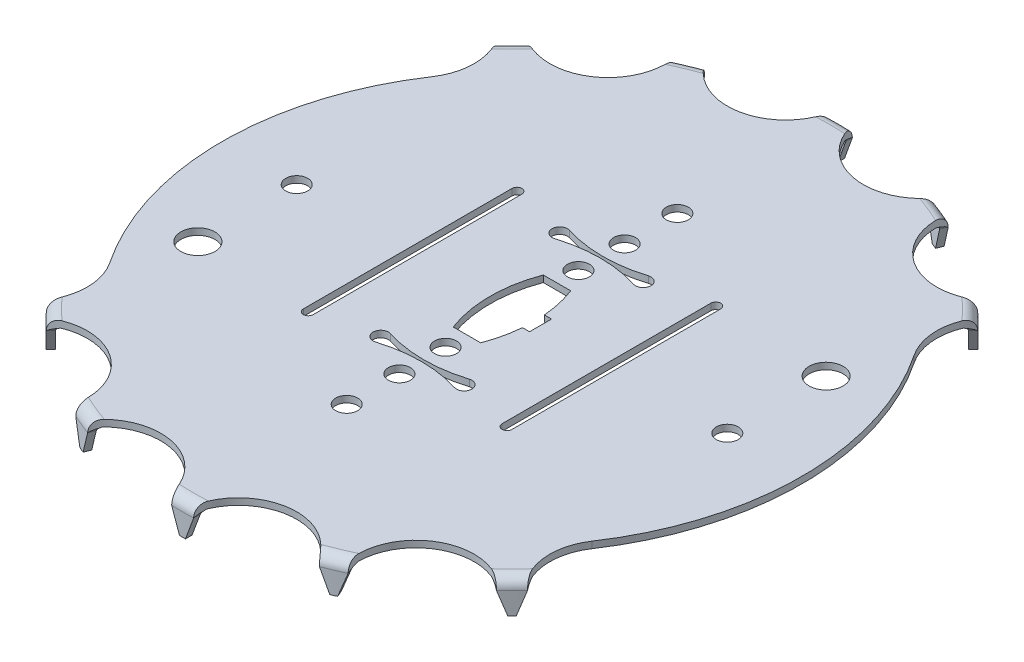
SolidWorks part; units mm, degrees
material "A-Glass Fiber"
ref_plane "Front Plane" through (0, 0, 0) normal (0, 0, 1) x (1, 0, 0)
ref_plane "Top Plane" through (0, 0, 0) normal (0, 1, 0) x (1, 0, 0)
ref_plane "Right Plane" through (0, 0, 0) normal (1, 0, 0) x (0, 0, -1)
ref_axis "Axis1" through (0, -1.5774, 0) along (0, 1, 0)
sketch "Sketch6" plane through (0, 0, 0) normal (0, 0, 1) x (1, 0, 0)
  line L0 (0, 0) -> (14.5, 0)
  line L1 (14.52, 0) -> (-14.52, 0) construction
  line L2 (15, -0.5) -> (15, -1.5)
  line L3 (0, -0.8514) -> (0, 0.8514) construction
  arc A0 (14.5, 0) -> (15, -0.5) centre (14.5, -0.5) cw
  point P8 (15, 0)
  dimension "D2" = 0.5
  dimension "D1" = 1.5
  dimension "D3" = 15
revolve "Revolve-Thin1" add sketch "Sketch6" angle 360 about axis through (0, -1.5774, 0) along (0, 1, 0)
sketch "Sketch1" plane through (0, 0, 0) normal (0, 1, 0) x (1, 0, 0)
  line L0 (-10.6066, 10.6066) -> (10.6066, -10.6066) construction
  line L1 (-5.7403, 13.8582) -> (5.7403, -13.8582) construction
  line L2 (5.7403, 13.8582) -> (-5.7403, -13.8582) construction
  line L3 (10.6066, 10.6066) -> (-10.6066, -10.6066) construction
  line L5 (0, -0.8514) -> (0, 0.8514) construction
  arc A0 (10.9543, 10.2472) -> (10.2472, 10.9543) centre (0, 0) ccw
  arc A1 (0.5, 14.9917) -> (-0.5, 14.9917) centre (0, 0) ccw
  arc A2 (-5.2751, -14.0418) -> (-0.5, -14.9917) centre (-3.0924, -15.5465) cw
  arc A3 (-10.2472, -10.9543) -> (-6.199, -13.6592) centre (-8.8064, -13.1797) cw
  arc A4 (0.5, -14.9917) -> (5.2751, -14.0418) centre (3.0924, -15.5465) cw
  arc A5 (6.199, -13.6592) -> (10.2472, -10.9543) centre (8.8064, -13.1797) cw
  arc A6 (10.9543, -10.2472) -> (10.9754, -7.3335) centre (13.1797, -8.8064) cw
  arc A7 (-10.9543, -10.2472) -> (-10.9754, -7.3335) centre (-13.1797, -8.8064) ccw
  arc A8 (-10.2472, 10.9543) -> (-6.199, 13.6592) centre (-8.8064, 13.1797) ccw
  arc A9 (-5.2751, 14.0418) -> (-0.5, 14.9917) centre (-3.0924, 15.5465) ccw
  arc A10 (0.5, 14.9917) -> (5.2751, 14.0418) centre (3.0924, 15.5465) ccw
  arc A11 (6.199, 13.6592) -> (10.2472, 10.9543) centre (8.8064, 13.1797) ccw
  arc A12 (10.9543, 10.2472) -> (10.9754, 7.3335) centre (13.1797, 8.8064) ccw
  arc A13 (-10.9543, 10.2472) -> (-10.9754, 7.3335) centre (-13.1797, 8.8064) cw
  arc A14 (6.199, 13.6592) -> (5.2751, 14.0418) centre (0, 0) ccw
  arc A15 (-5.2751, 14.0418) -> (-6.199, 13.6592) centre (0, 0) ccw
  arc A16 (-10.2472, 10.9543) -> (-10.9543, 10.2472) centre (0, 0) ccw
  arc A17 (-6.199, -13.6592) -> (-5.2751, -14.0418) centre (0, 0) ccw
  arc A18 (-0.5, -14.9917) -> (0.5, -14.9917) centre (0, 0) ccw
  arc A19 (5.2751, -14.0418) -> (6.199, -13.6592) centre (0, 0) ccw
  arc A20 (10.2472, -10.9543) -> (10.9543, -10.2472) centre (0, 0) ccw
  arc A21 (-10.9754, 7.3335) -> (-10.9754, -7.3335) centre (0, 0) ccw
  arc A22 (10.9754, -7.3335) -> (10.9754, 7.3335) centre (0, 0) ccw
  arc A23 (-10.9543, -10.2472) -> (-10.2472, -10.9543) centre (0, 0) ccw
  circle A24 centre (0, 0) radius 13.2 construction
  dimension "D2" = 30
  dimension "D3" = 45
  dimension "D9" = 0.5
  dimension "D22" = 0.5
  dimension "D25" = 13.2
  dimension "D26" = 15
  dimension "D4" = 45
  dimension "D5" = 0.5
  dimension "D6" = 22.5
  dimension "D7" = 0.5
  dimension "D8" = 0.5
  dimension "D10" = 1
  dimension "D11" = 0.5
  dimension "D12" = 0.5
  dimension "D13" = 0.5
  dimension "D14" = 0.5
  dimension "D15" = 0.5
  dimension "D16" = 45
  dimension "D17" = 0.5
  dimension "D18" = 0.5
  dimension "D19" = 0.5
  dimension "D20" = 0.5
  dimension "D21" = 0.5
  dimension "D23" = 0.5
  dimension "D24" = 0.5
extrude "Extrude3" cut sketch "Sketch1" against normal through all flip side to cut
ref_plane "Plane2" through (0, 0, 15) normal (0, 0, 1) x (1, 0, 0)
sketch "Sketch8" plane through (0, 0, 15) normal (0, 0, 1) x (1, 0, 0)
  line L0 (-0.5, -0.5) -> (-0.136, -1.5)
  line L1 (-0.5, -1.5) -> (0.5, -1.5) construction
  line L2 (-0.136, -1.5) -> (0.136, -1.5)
  line L3 (0.136, -1.5) -> (0.5, -0.5)
  line L4 (0.6632, -0.3) -> (0.6632, -1.8)
  line L5 (-0.6632, -0.3) -> (-0.6632, -1.8)
  line L6 (-0.6632, -1.8) -> (0.6632, -1.8)
  line L7 (14.52, 0) -> (-14.52, 0) construction
  arc A0 (0.5, -0.5) -> (0.6632, -0.3) centre (0.8686, -0.6342) cw
  arc A1 (-0.5, -0.5) -> (-0.6632, -0.3) centre (-0.8686, -0.6342) ccw
  dimension "D1" = 40
  dimension "D2" = 1.8
extrude "Extrude4" cut sketch "Sketch8" against normal blind 2
pattern_circular "CirPattern1" count 16 over 360 about axis through (0, 0, 0) along (0, 1, 0) of "Extrude4"
sketch "Sketch10" plane through (0, 0, 0) normal (0, 1, 0) x (1, 0, 0)
  line L0 (0, -0.825) -> (0, 0.825) construction
  line L1 (-0.825, 0) -> (0.825, 0) construction
  circle A0 centre (0, 3.025) radius 0.5
  circle A1 centre (0, 5.125) radius 0.5
  circle A2 centre (0, 7.525) radius 0.5
  circle A3 centre (0, -3.025) radius 0.5
  circle A4 centre (0, -5.125) radius 0.5
  circle A5 centre (0, -7.525) radius 0.5
  dimension "D1" = 1
  dimension "D2" = 6.05
  dimension "D3" = 15.05
  dimension "D4" = 7.525
  dimension "D5" = 3.025
  dimension "D6" = 10.25
  dimension "D7" = 5.125
extrude "Extrude5" cut sketch "Sketch10" against normal through all
sketch "Sketch11" plane through (0, 0, 0) normal (0, 1, 0) x (1, 0, 0)
  line L0 (-4.525, 4.75) -> (-4.525, -4.75) construction
  line L1 (-4.3, 4.75) -> (-4.3, -4.75)
  line L2 (-4.75, 4.75) -> (-4.75, -4.75)
  line L3 (4.525, 4.75) -> (4.525, -4.75) construction
  line L4 (4.75, 4.75) -> (4.75, -4.75)
  line L5 (4.3, 4.75) -> (4.3, -4.75)
  line L6 (-0.825, 0) -> (0.825, 0) construction
  line L7 (0, -0.825) -> (0, 0.825) construction
  arc A0 (-4.3, 4.75) -> (-4.75, 4.75) centre (-4.525, 4.75) ccw
  arc A1 (-4.75, -4.75) -> (-4.3, -4.75) centre (-4.525, -4.75) ccw
  arc A2 (4.75, 4.75) -> (4.3, 4.75) centre (4.525, 4.75) ccw
  arc A3 (4.3, -4.75) -> (4.75, -4.75) centre (4.525, -4.75) ccw
  arc A4 (-1.7953, 4.409) -> (-1.7953, 3.741) centre (-1.9, 4.075) ccw
  arc A5 (1.7953, 3.741) -> (1.7953, 4.409) centre (1.9, 4.075) ccw
  arc A6 (1.7953, -4.409) -> (1.7953, -3.741) centre (1.9, -4.075) ccw
  arc A7 (-1.7953, -3.741) -> (-1.7953, -4.409) centre (-1.9, -4.075) ccw
  arc A8 (-1.7953, 4.409) -> (1.7953, 4.409) centre (0, 10.1341) ccw
  arc A9 (1.7953, 3.741) -> (-1.7953, 3.741) centre (0, -1.9841) ccw
  arc A10 (-1.7953, -3.741) -> (1.7953, -3.741) centre (0, 1.9841) ccw
  arc A11 (-1.7953, -4.409) -> (1.7953, -4.409) centre (0, -10.1341) cw
  circle A12 centre (0, 3.025) radius 0.5 construction
  point P2 (-4.525, 0)
  point P7 (4.525, 0)
  dimension "D7" = 4.075
  dimension "D8" = 1.05
  dimension "D10" = 3.8
  dimension "D9" = 0.35
  dimension "D11" = 6
  dimension "D12" = 6
  dimension "D1" = 0.45
  dimension "D2" = 9.5
  dimension "D3" = 4.75
  dimension "D4" = 8.6
  dimension "D5" = 4.3
  dimension "D6" = 9.5
  dimension "D13" = 4.075
extrude "Extrude6" cut sketch "Sketch11" against normal blind 9.8
sketch "Sketch12" plane through (0, 0, 0) normal (0, 1, 0) x (1, 0, 0)
  line L0 (-0.825, 0) -> (0.825, 0) construction
  line L1 (0, -0.825) -> (0, 0.825) construction
  circle A0 centre (-9.8, 0) radius 0.5
  circle A1 centre (9.8, 0) radius 0.5
  circle A2 centre (9.8, 4.5) radius 0.775
  circle A3 centre (-9.8, -4.5) radius 0.775
  dimension "D1" = 1
  dimension "D2" = 1.55
  dimension "D3" = 4.5
  dimension "D4" = 4.5
  dimension "D5" = 19.6
  dimension "D6" = 9.8
extrude "Extrude7" cut sketch "Sketch12" against normal blind 9.8
sketch "Sketch13" plane through (0, 0, 0) normal (0, 1, 0) x (1, 0, 0)
  line L0 (-0.625, -2.05) -> (0.625, -2.05)
  line L1 (-0.625, 2.05) -> (0.625, 2.05)
  line L2 (-0.825, 0) -> (0.825, 0) construction
  line L3 (0, -0.825) -> (0, 0.825) construction
  line L4 (0.9778, 0.5) -> (1.3, 0.5)
  line L5 (1.3, 0.5) -> (1.3, -0.5)
  line L6 (1.3, -0.5) -> (0.9778, -0.5)
  arc A0 (0.625, 2.05) -> (0.9778, 0.5) centre (-4.8006, 0) cw
  arc A1 (-0.625, 2.05) -> (-0.9994, 0) centre (4.8006, 0) ccw
  arc A2 (-0.9994, 0) -> (-0.625, -2.05) centre (4.8006, 0) ccw
  arc A3 (0.9778, -0.5) -> (0.625, -2.05) centre (-4.8006, 0) cw
  dimension "D4" = 5.8
  dimension "D1" = 4.1
  dimension "D2" = 1.25
  dimension "D3" = 0.625
  dimension "D5" = 1.3
  dimension "D6" = 1
  dimension "D7" = 0.5
extrude "Extrude8" cut sketch "Sketch13" against normal blind 9.8
